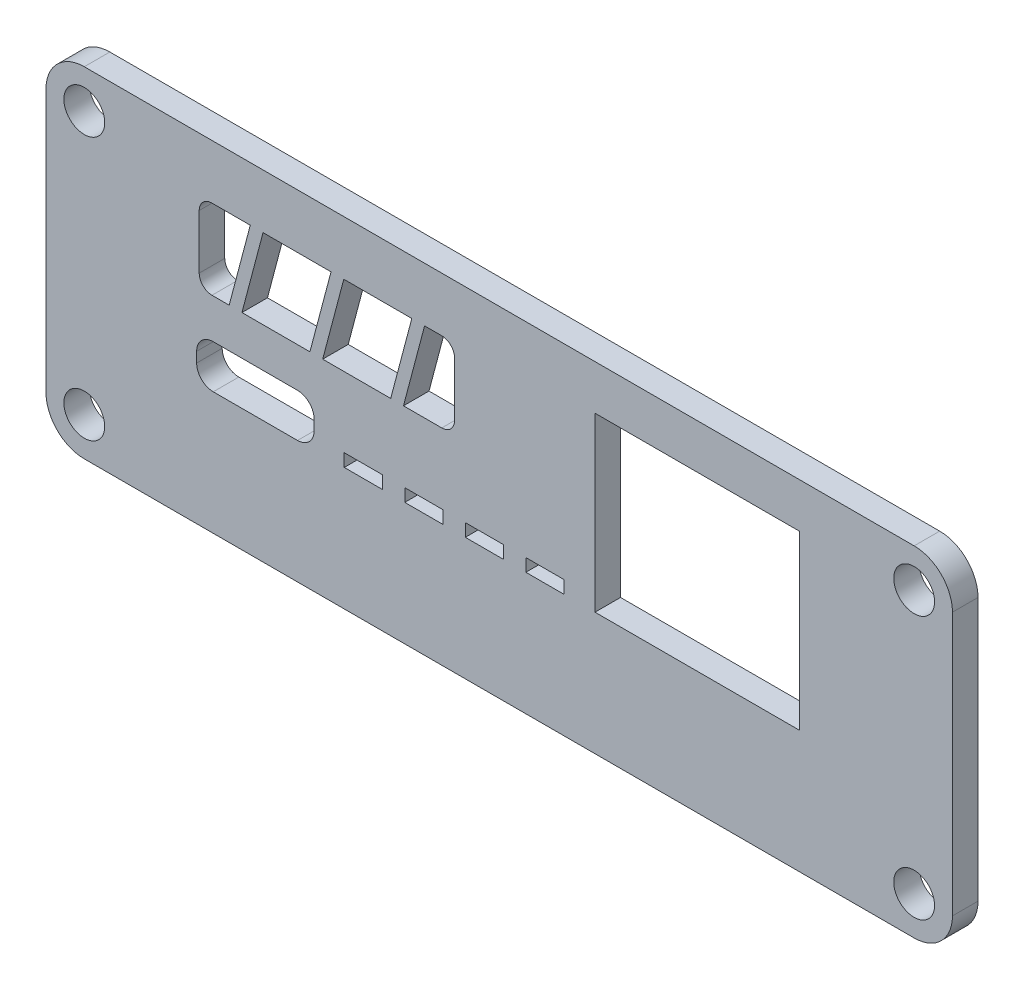
SolidWorks part; units mm, degrees
ref_plane "前视基准面" through (0, 0, 0) normal (0, 0, 1) x (1, 0, 0)
ref_plane "上视基准面" through (0, 0, 0) normal (0, 1, 0) x (1, 0, 0)
ref_plane "右视基准面" through (0, 0, 0) normal (1, 0, 0) x (0, 0, -1)
sketch "草图1" plane through (0, 0, 0) normal (0, 0, 1) x (1, 0, 0)
  line L1 (3, 0) -> (68, 0)
  line L2 (0, -3) -> (0, -23.6)
  line L3 (3, -26.6) -> (68, -26.6)
  line L4 (71, -3) -> (71, -23.6)
  arc A0 (0, -23.6) -> (3, -26.6) centre (3, -23.6) ccw
  arc A1 (68, -26.6) -> (71, -23.6) centre (68, -23.6) ccw
  arc A2 (68, 0) -> (71, -3) centre (68, -3) cw
  arc A3 (3, 0) -> (0, -3) centre (3, -3) ccw
  circle A4 centre (3, -3) radius 1.6
  circle A5 centre (68, -3) radius 1.6
  circle A6 centre (68, -23.6) radius 1.6
  circle A7 centre (3, -23.6) radius 1.6
  point P9 (71, -26.6)
  point P12 (71, 0)
  point P15 (0, 0)
  dimension "D3" = 3
  dimension "D1" = 71
  dimension "D2" = 26.6
extrude "凸台-拉伸1" add sketch "草图1" along normal blind 2
sketch "草图2" plane through (0, 0, 0) normal (0, 0, -1) x (-1, 0, 0)
  line L0 (-71, -23.6) -> (-71, -3) construction
  line L1 (-59, -3.5) -> (-43, -3.5)
  line L2 (-59, -3.5) -> (-59, -17)
  line L3 (-59, -17) -> (-43, -17)
  line L4 (-43, -3.5) -> (-43, -17)
  line L5 (-68, 0) -> (-3, 0) construction
  line L6 (0, -3) -> (0, -23.6) construction
  line L7 (-19.7, -17) -> (-13.1, -17)
  line L8 (-21, -15.7) -> (-21, -14.9)
  line L9 (-19.7, -13.6) -> (-13.1, -13.6)
  line L10 (-11.8, -15.7) -> (-11.8, -14.9)
  line L16 (-40.584, -16) -> (-37.584, -16)
  line L17 (-40.584, -16) -> (-40.584, -17)
  line L18 (-40.584, -17) -> (-37.584, -17)
  line L19 (-37.584, -16) -> (-37.584, -17)
  line L20 (-35.843, -16) -> (-32.843, -16)
  line L21 (-35.843, -16) -> (-35.843, -17)
  line L22 (-35.843, -17) -> (-32.843, -17)
  line L23 (-32.843, -16) -> (-32.843, -17)
  line L24 (-31.101, -16) -> (-28.101, -16)
  line L25 (-31.101, -16) -> (-31.101, -17)
  line L26 (-31.101, -17) -> (-28.101, -17)
  line L27 (-28.101, -16) -> (-28.101, -17)
  line L28 (-26.36, -16) -> (-23.36, -16)
  line L29 (-26.36, -16) -> (-26.36, -17)
  line L30 (-26.36, -17) -> (-23.36, -17)
  line L31 (-23.36, -16) -> (-23.36, -17)
  arc A0 (-19.7, -17) -> (-21, -15.7) centre (-19.7, -15.7) cw
  arc A1 (-13.1, -17) -> (-11.8, -15.7) centre (-13.1, -15.7) ccw
  arc A2 (-13.1, -13.6) -> (-11.8, -14.9) centre (-13.1, -14.9) cw
  arc A3 (-21, -14.9) -> (-19.7, -13.6) centre (-19.7, -14.9) cw
  point P34 (-11.8, -17)
  point P37 (-11.8, -13.6)
  point P40 (-21, -13.6)
  dimension "D9" = 1.3
  dimension "D1" = 12
  dimension "D2" = 28
  dimension "D3" = 13.5
  dimension "D4" = 3.5
  dimension "D5" = 9.2
  dimension "D6" = 3.4
  dimension "D7" = 17
  dimension "D8" = 21
  dimension "D12" = 3
  dimension "D14" = 3
  dimension "D16" = 3
  dimension "D17" = 3
extrude "切除-拉伸2" cut sketch "草图2" against normal blind 2
sketch "草图3" plane through (0, 0, 2) normal (0, 0, 1) x (1, 0, 0)
  line L0 (68, 0) -> (3, 0) construction
  line L1 (12, -1.75) -> (32, -1.75)
  line L2 (12, -1.75) -> (12, -4.25)
  line L3 (12, -4.25) -> (32, -4.25)
  line L4 (32, -1.75) -> (32, -4.25)
  line L5 (0, -3) -> (0, -23.6) construction
  dimension "D1" = 20
  dimension "D2" = 2.5
  dimension "D3" = 1.75
  dimension "D4" = 12
  dimension "D5" = 11
extrude "凸台-拉伸2" add sketch "草图3" along normal blind 20
sketch "草图5" plane through (0, 0, 2) normal (0, 0, 1) x (1, 0, 0)
  line L0 (16, -4.25) -> (14.3472, -10.5)
  line L1 (13, -4.25) -> (31, -4.25)
  line L2 (12, -5.25) -> (12, -9.5)
  line L3 (13, -10.5) -> (31, -10.5)
  line L4 (32, -5.25) -> (32, -9.5)
  line L5 (16, -4.25) -> (17, -4.25)
  line L6 (12, -4.25) -> (32, -4.25) construction
  line L7 (14.3472, -10.5) -> (15.3472, -10.5)
  line L8 (12, -1.75) -> (12, -4.25) construction
  line L9 (17, -4.25) -> (15.3472, -10.5)
  line L10 (12, -4.25) -> (32, -4.25) construction
  line L11 (22.325, -4.25) -> (20.6722, -10.5)
  line L12 (22.325, -4.25) -> (23.325, -4.25)
  line L13 (20.6722, -10.5) -> (21.6722, -10.5)
  line L14 (23.325, -4.25) -> (21.6722, -10.5)
  line L15 (28.6528, -4.25) -> (27, -10.5)
  line L16 (28.6528, -4.25) -> (29.6528, -4.25)
  line L17 (27, -10.5) -> (28, -10.5)
  line L18 (29.6528, -4.25) -> (28, -10.5)
  arc A0 (31, -4.25) -> (32, -5.25) centre (31, -5.25) cw
  arc A1 (31, -10.5) -> (32, -9.5) centre (31, -9.5) ccw
  arc A2 (12, -9.5) -> (13, -10.5) centre (13, -9.5) ccw
  arc A3 (13, -4.25) -> (12, -5.25) centre (13, -5.25) ccw
  point P11 (32, -4.25)
  point P16 (12, -10.5)
  point P19 (12, -4.25)
  line M61 (32, -4.25) -> (12, -4.25)
  dimension "D3" = 1
  dimension "D1" = 6.25
  dimension "D2" = 20
  dimension "D4" = 1
  dimension "D5" = 3
  dimension "D6" = 18
  dimension "D7" = 3
  dimension "D8" = 1
  dimension "D9" = 6.325
  dimension "D10" = 6.3278
extrude "切除-拉伸3" cut sketch "草图5" against normal blind 20 contours A3 L2 A2 L3 L0 M61 | L11 L1 L9 L3 | L15 L1 L14 L3 | L3 A1 L4 A0 L18 M61
sketch "草图6" plane through (0, 0, 22) normal (0, 0, 1) x (1, 0, 0)
  line L1 (12, -1.75) -> (32, -1.75)
  line L2 (12, -1.75) -> (12, -4.25)
  line L3 (12, -4.25) -> (32, -4.25)
  line L4 (32, -1.75) -> (32, -4.25)
extrude "切除-拉伸4" cut sketch "草图6" against normal blind 20
